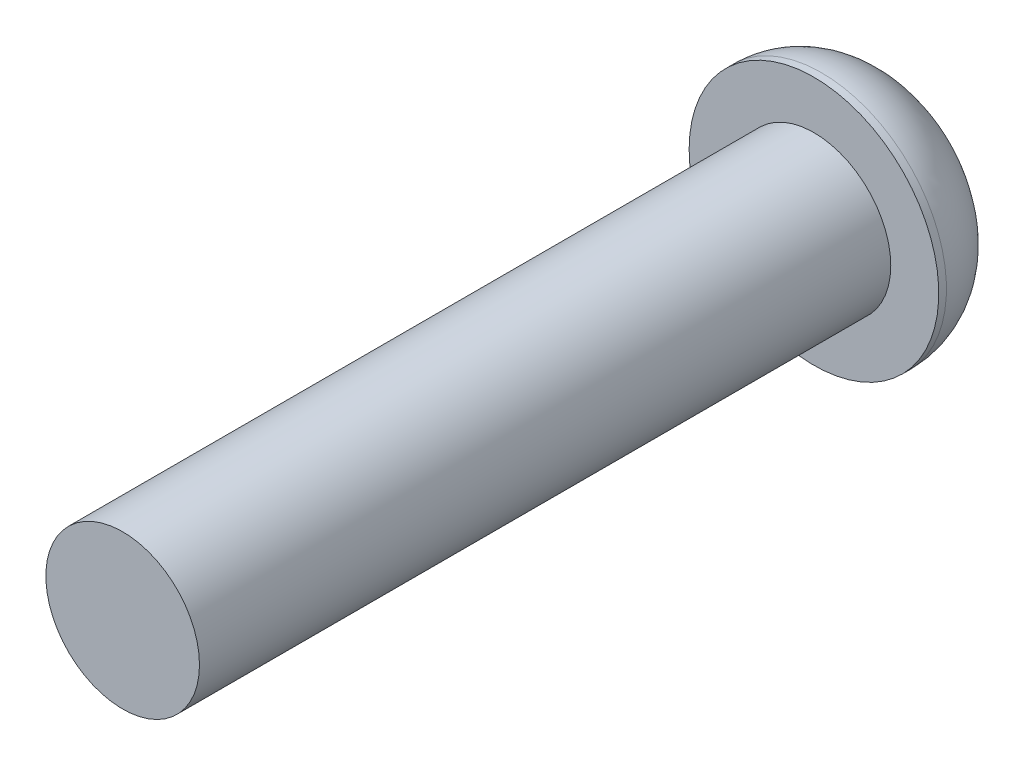
SolidWorks part; units mm, degrees
ref_plane "前视基准面" through (0, 0, 0) normal (0, 0, 1) x (1, 0, 0)
ref_plane "上视基准面" through (0, 0, 0) normal (0, 1, 0) x (1, 0, 0)
ref_plane "右视基准面" through (0, 0, 0) normal (1, 0, 0) x (0, 0, -1)
sketch "草图1" plane through (0, 0, 0) normal (0, 0, 1) x (1, 0, 0)
  circle A0 centre (0, 0) radius 2
  dimension "D1" = 4
extrude "凸台-拉伸1" add sketch "草图1" along normal blind 18
sketch "草图2" plane through (0, 0, 0) normal (0, 0, -1) x (-1, 0, 0)
  circle A0 centre (0, 0) radius 3.25
  dimension "D1" = 6.5
extrude "凸台-拉伸2" add sketch "草图2" along normal blind 2.2
fillet "圆角1" radius 2 1 edges at (-3.25, 0, -2.2)
sketch "草图3" plane through (0, 0, -2.2) normal (0, 0, -1) x (-1, 0, 0)
  line L0 (0, 3.24) -> (0, -3.24) construction
  line L1 (-3.24, 0) -> (3.24, 0) construction
  line L2 (-3.24, 0.25) -> (3.24, 0.25) construction
  line L3 (0.25, 3.24) -> (0.25, -3.24) construction
  line L4 (-3.24, -0.25) -> (3.24, -0.25) construction
  line L5 (-0.25, 3.24) -> (-0.25, -3.24) construction
  line L7 (3.24, 0.25) -> (3.24, -0.25)
  line L8 (-0.25, 3.24) -> (0.25, 3.24)
  line L10 (-0.25, 3.24) -> (-0.25, 0.25)
  line L11 (0.25, 3.24) -> (0.25, 0.25)
  line L12 (3.24, 0.25) -> (0.25, 0.25)
  line L13 (3.24, -0.25) -> (0.25, -0.25)
  line L15 (0.25, -3.24) -> (0.25, -0.25)
  line L16 (-0.25, -3.24) -> (-0.25, -0.25)
  line L17 (0.25, -3.24) -> (-0.25, -3.24)
  line L18 (-3.24, -0.25) -> (-0.25, -0.25)
  line L19 (-3.24, 0.25) -> (-0.25, 0.25)
  line L20 (-3.24, -0.25) -> (-3.24, 0.25)
  line L21 (3.24, 0.25) -> (3.24, -0.25) [skipped]
  circle A1 centre (0, 0) radius 3.24 construction
  dimension "D1" = 0.25
  dimension "D2" = 0.25
  dimension "D3" = 4
extrude "切除-拉伸1" cut sketch "草图3" against normal blind 0.5
